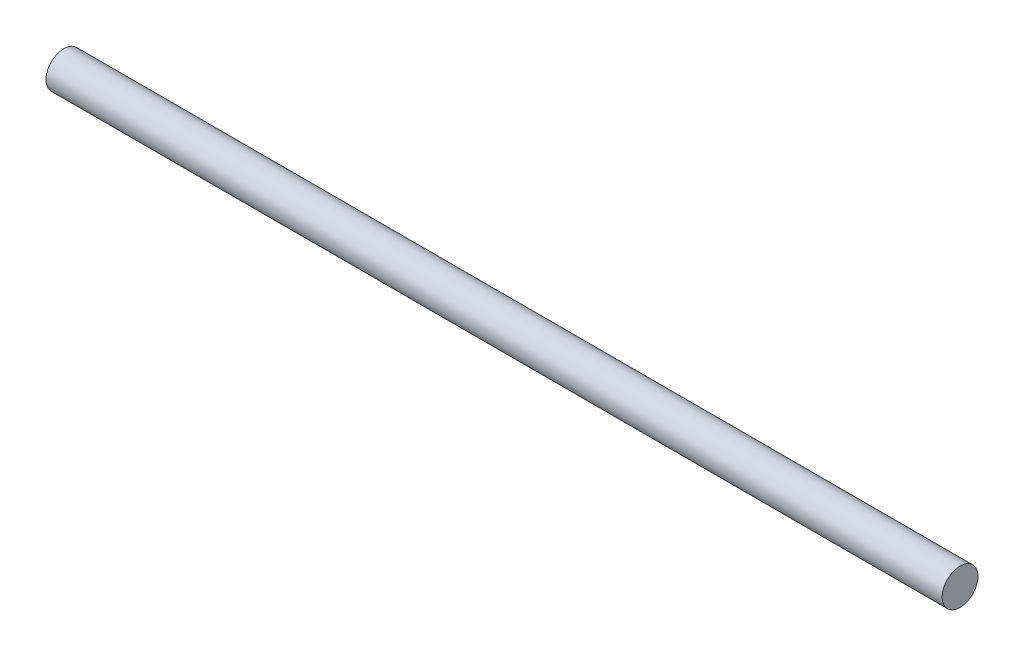
SolidWorks part; units mm, degrees
material "Acero inoxidable al cromo"
ref_plane "Alzado" through (0, 0, 0) normal (0, 0, 1) x (1, 0, 0)
ref_plane "Planta" through (0, 0, 0) normal (0, 1, 0) x (1, 0, 0)
ref_plane "Vista lateral" through (0, 0, 0) normal (1, 0, 0) x (0, 0, -1)
sketch "Croquis1" plane through (0, 0, 0) normal (1, 0, 0) x (0, 0, -1)
  circle A0 centre (0, 0) radius 10
extrude "Saliente-Extruir1" add sketch "Croquis1" along normal blind 500
